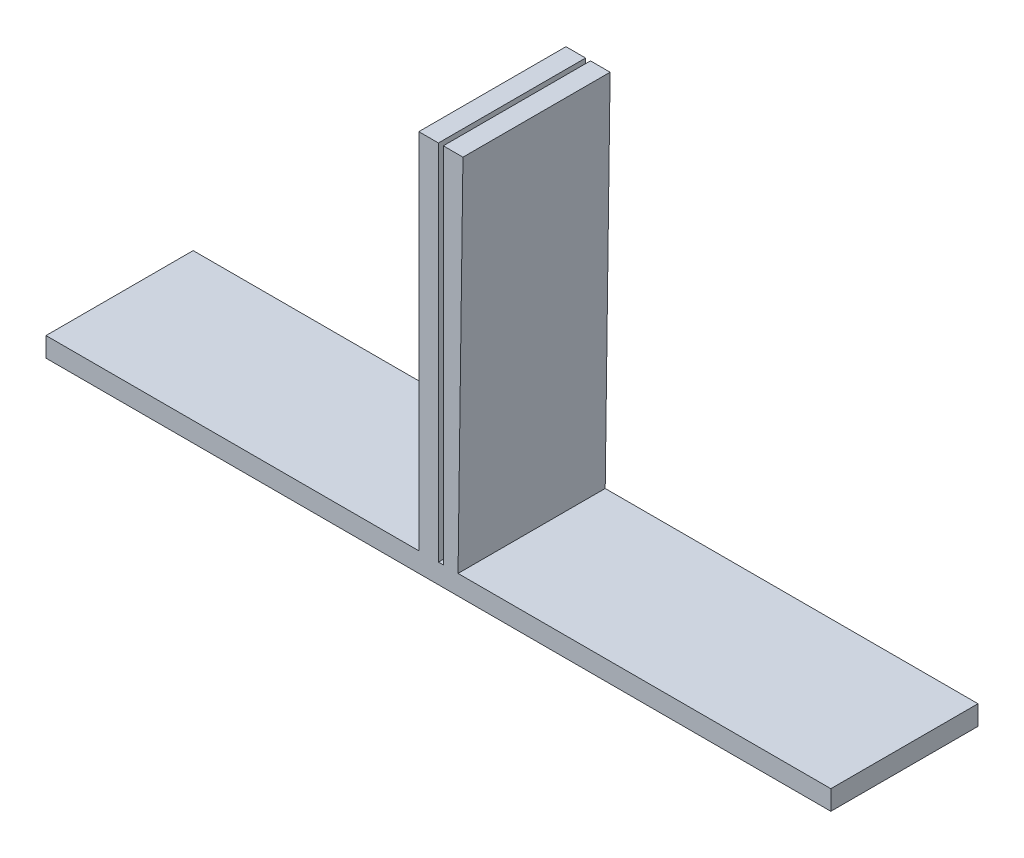
SolidWorks part; units mm, degrees
ref_plane "Plan de face" through (0, 0, 0) normal (0, 0, 1) x (1, 0, 0)
ref_plane "Plan de dessus" through (0, 0, 0) normal (0, 1, 0) x (1, 0, 0)
ref_plane "Plan de droite" through (0, 0, 0) normal (1, 0, 0) x (0, 0, -1)
sketch "Esquisse1" plane through (0, 0, 0) normal (0, 0, 1) x (1, 0, 0)
  line L0 (37.1967, 0) -> (-42.8033, 0)
  line L1 (37.1967, 0) -> (37.1967, 2)
  line L2 (37.1967, 2) -> (-0.8033, 2)
  line L3 (-0.8033, 2) -> (-0.3033, 38.9966)
  line L4 (-0.3033, 38.9966) -> (-2.3033, 39)
  line L5 (-2.3033, 39) -> (-2.3033, 2)
  line L6 (-2.3033, 2) -> (-2.8033, 2)
  line L7 (-2.8033, 2) -> (-2.8033, 39)
  line L8 (-2.8033, 39) -> (-4.8033, 39)
  line L9 (-4.8033, 39) -> (-4.8033, 2)
  line L10 (-4.8033, 2) -> (-42.8033, 2)
  line L11 (-42.8033, 2) -> (-42.8033, 0)
  dimension "D1" = 80
  dimension "D2" = 37
  dimension "D3" = 37
  dimension "D4" = 2
  dimension "D5" = 2
  dimension "D6" = 37
  dimension "D7" = 37
  dimension "D8" = 0.5
  dimension "D9" = 2
  dimension "D10" = 2
extrude "Boss.-Extru.1" add sketch "Esquisse1" along normal blind 15
